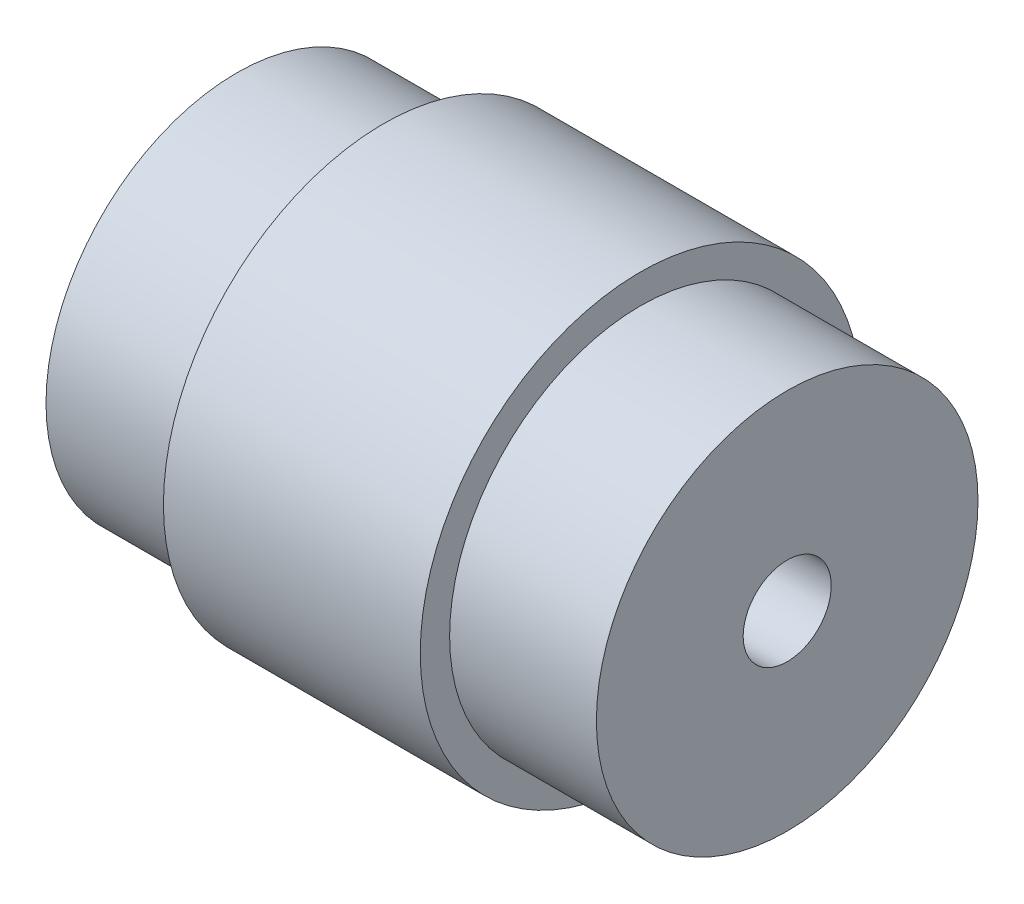
SolidWorks part; units mm, degrees
ref_plane "Front Plane" through (0, 0, 0) normal (0, 0, 1) x (1, 0, 0)
ref_plane "Top Plane" through (0, 0, 0) normal (0, 1, 0) x (1, 0, 0)
ref_plane "Right Plane" through (0, 0, 0) normal (1, 0, 0) x (0, 0, -1)
sketch "Sketch1" plane through (0, 0, 0) normal (0, 0, 1) x (1, 0, 0)
  line L0 (0, 3) -> (0, 13)
  line L1 (0, 13) -> (10, 13)
  line L2 (10, 13) -> (10, 15)
  line L3 (10, 15) -> (27.5, 15)
  line L4 (27.5, 15) -> (27.5, 13)
  line L5 (27.5, 13) -> (37.5, 13)
  line L6 (37.5, 13) -> (37.5, 3)
  line L8 (0, 3) -> (37.5, 3)
  line L9 (0, 0) -> (39.7868, 0) construction
  dimension "D1" = 37.5
  dimension "D2" = 3
  dimension "D3" = 2
  dimension "D4" = 13
  dimension "D5" = 10
revolve "Revolve1" add sketch "Sketch1" angle 360 about L9
